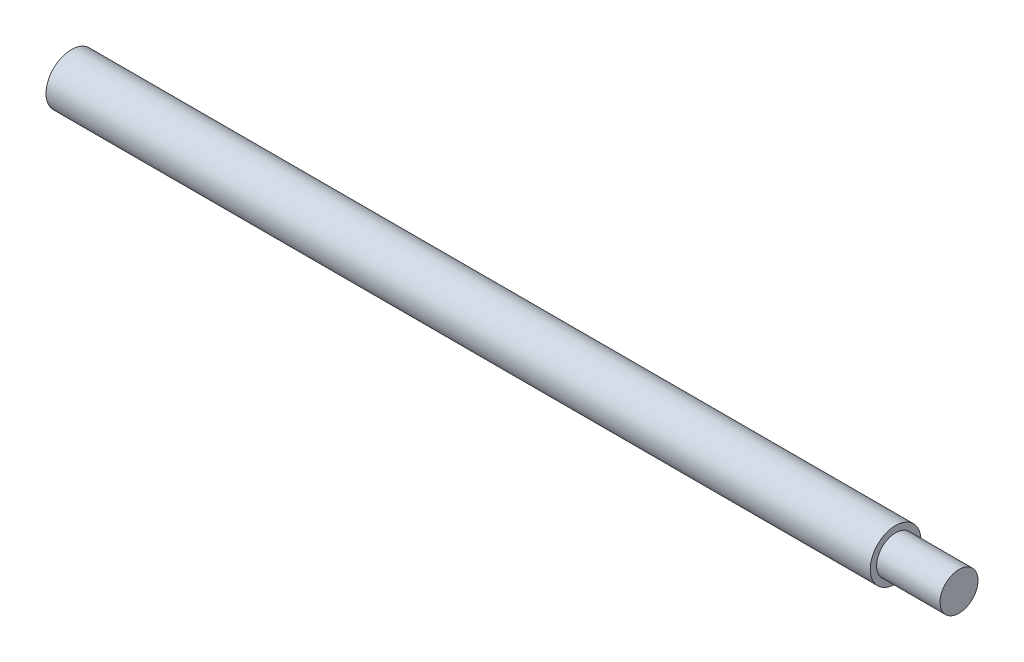
SolidWorks part; units mm, degrees
material "AISI 1045 Steel, cold drawn"
ref_plane "Front Plane" through (0, 0, 0) normal (0, 0, 1) x (1, 0, 0)
ref_plane "Top Plane" through (0, 0, 0) normal (0, 1, 0) x (1, 0, 0)
ref_plane "Right Plane" through (0, 0, 0) normal (1, 0, 0) x (0, 0, -1)
sketch "Sketch1" plane through (0, 0, 0) normal (1, 0, 0) x (0, 0, -1)
  circle A0 centre (0, 0) radius 4
  dimension "D1" = 8
extrude "Boss-Extrude1" add sketch "Sketch1" along normal mid plane 140
cosmetic thread "Cosmetic Thread10" parameters "D2"=6.619
sketch "Sketch7" plane through (70, 0, 0) normal (-1, 0, 0) x (0, 0, 1)
  circle A0 centre (0, 0) radius 3
  dimension "D1" = 6
extrude "Cut-Extrude4" cut sketch "Sketch7" along normal blind 10 flip side to cut contours A0
cosmetic thread "Cosmetic Thread9" parameters "D1"=10, "D2"=4.891
